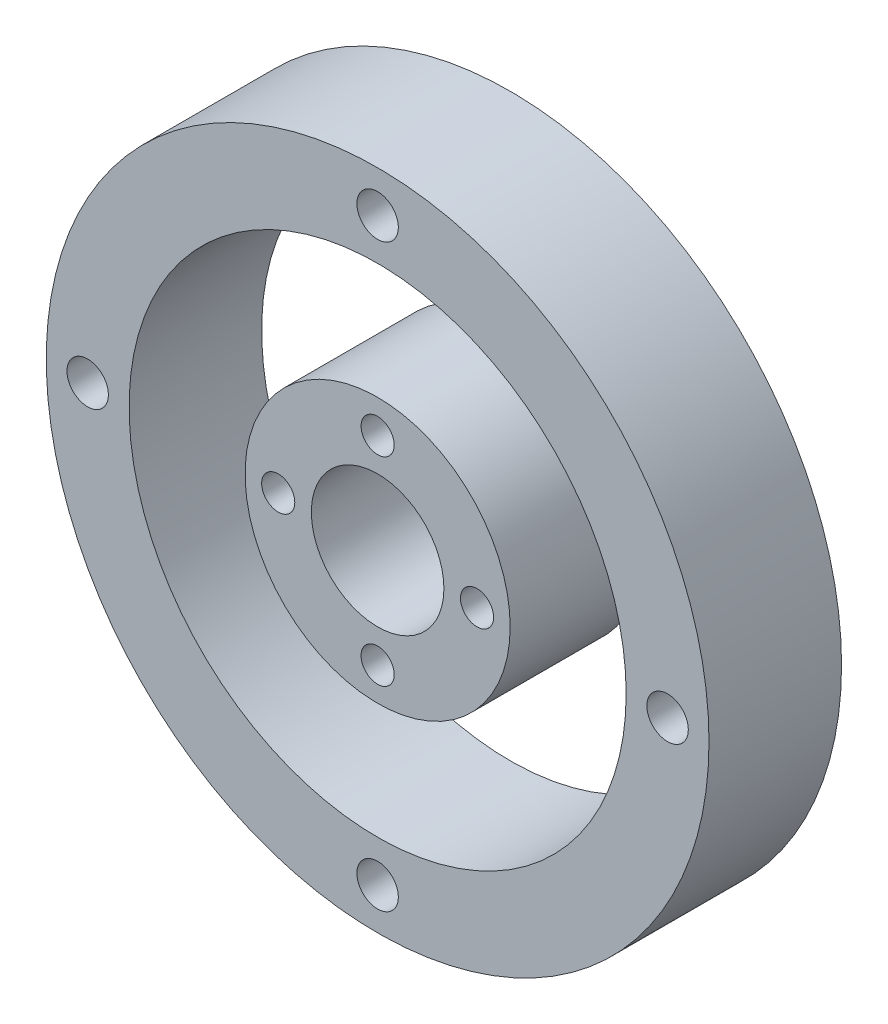
SolidWorks part; units mm, degrees
ref_plane "Front Plane" through (0, 0, 0) normal (0, 0, 1) x (1, 0, 0)
ref_plane "Top Plane" through (0, 0, 0) normal (0, 1, 0) x (1, 0, 0)
ref_plane "Right Plane" through (0, 0, 0) normal (1, 0, 0) x (0, 0, -1)
sketch "Sketch1" plane through (0, 0, 0) normal (0, 0, 1) x (1, 0, 0)
  circle A0 centre (0, 0) radius 20
  circle A2 centre (0, 0) radius 17.5 construction
  circle A3 centre (0, 17.5) radius 1.25
  circle A4 centre (0, 0) radius 4
  circle A5 centre (0, 0) radius 8
  circle A6 centre (0, 0) radius 6 construction
  circle A7 centre (0, 6) radius 1
  circle A8 centre (17.5, 0) radius 1.25
  circle A9 centre (0, -17.5) radius 1.25
  circle A10 centre (-17.5, 0) radius 1.25
  circle A11 centre (6, 0) radius 1
  circle A12 centre (0, -6) radius 1
  circle A13 centre (-6, 0) radius 1
  circle A14 centre (0, 0) radius 15
  point P24 (0, 0)
  point P31 (0, 0)
  dimension "D1" = 40
  dimension "D2" = 5
  dimension "D4" = 2.5
  dimension "D5" = 8
  dimension "D8" = 2
  dimension "D3" = 2.5
  dimension "D6" = 4
  dimension "D7" = 2
  dimension "D9" = 4
  dimension "D10" = 4
extrude "Boss-Extrude1" add sketch "Sketch1" along normal blind 8
sketch "Sketch2" plane through (0, 0, 0) normal (0, 0, 1) x (1, 0, 0)
  line L0 (0, 0) -> (9.9197, 23.9483) construction
  line L1 (0, 0) -> (27.8891, 11.5521) construction
  line L2 (0, -4.4) -> (0, 4.4) construction
  circle A0 centre (0, 0) radius 15 construction
  circle A1 centre (0, 0) radius 8 construction
  spline S0 degree 3 poles (5.7403, 13.8582) (5.09, 12.3149) (4.726, 10.9228) (5.5637, 9.028) (8.0382, 8.1721) (8.9429, 8.1491) (10.1095, 7.3389) (10.6969, 5.9652) (10.3809, 4.7791) (8.944, 3.6747) (7.391, 3.0615) knots 0 0 0 0 0.11371 0.147633 0.339231 0.581235 0.626011 0.76911 0.808298 1 1 1 1
  spline S1 degree 1 poles (6.6618, 13.4699) (7.7583, 2.1314) knots 0 0 1 1 construction
  spline S2 degree 3 poles (6.6618, 13.4699) (6.5805, 13.277) (6.4164, 12.8727) (6.1657, 12.1851) (5.9604, 11.4679) (5.9042, 10.8701) (5.9647, 10.5415) (6.2772, 10.0687) (6.8003, 9.7058) (7.47, 9.4469) (8.1205, 9.2804) (8.6473, 9.1623) (9.1153, 9.0375) (9.5149, 8.8829) (9.8265, 8.7257) (10.1213, 8.5574) (10.5738, 8.1985) (10.9372, 7.7065) (11.2173, 7.1856) (11.4374, 6.6183) (11.5773, 6.0395) (11.6015, 5.3632) (11.342, 4.6898) (10.975, 4.2055) (10.3555, 3.5852) (9.5441, 3.0062) (8.575, 2.4797) (8.03, 2.2386) (7.7583, 2.1314) knots 0 0 0 0 0.015625 0.03125 0.0625 0.09375 0.125 0.1875 0.25 0.3125 0.375 0.4375 0.5 0.53125 0.5625 0.59375 0.625 0.65625 0.6875 0.71875 0.75 0.78125 0.8125 0.84375 0.875 0.9375 0.96875 1 1 1 1
  point P8 (5.0466, 9.3616)
  point P10 (7.5253, 8.4373)
  point P12 (10.7183, 5.6225)
  point P14 (7.6094, 8.5424)
  point P16 (9.626, 7.5761)
  point P17 (0, 0)
  point P22 (7.2312, 8.5424)
  point P23 (9.731, 7.7021)
  point P24 (11.0288, 5.7587)
  point P25 (9.7344, 7.8278)
  point P28 (4.8185, 9.4405)
  point P29 (7.8502, 1.8988)
  point P30 (7.391, 3.0615)
  point P31 (7.4835, 8.4153)
  point P32 (9.7209, 7.6695)
  point P33 (5.0409, 9.9256)
  point P34 (10.9515, 5.3948)
  point P35 (10.0912, 7.3625)
  point P36 (10.5557, 5.4683)
  point P37 (9.6971, 7.6149)
  point P38 (5.0269, 10.2738)
  point P39 (0, 0)
  dimension "D1" = 22.5
  dimension "D2" = 45
  dimension "D3" = 1
